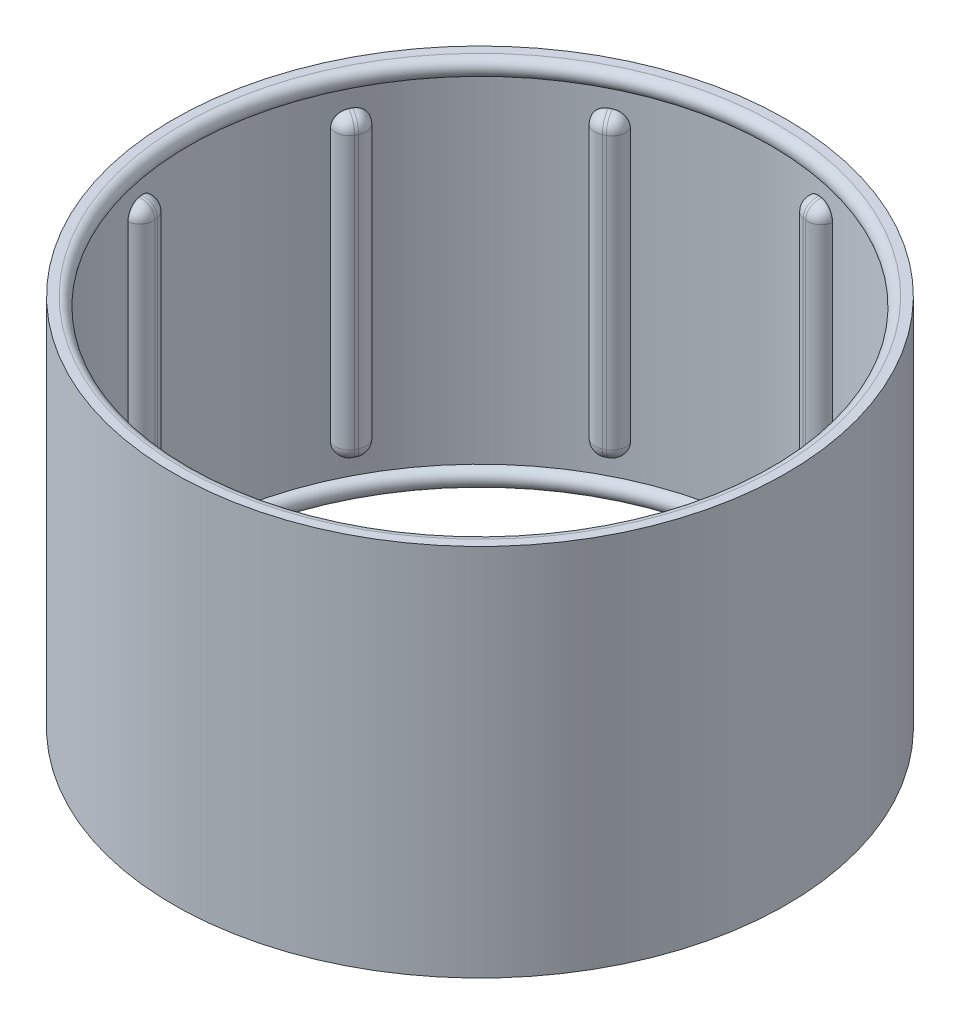
SolidWorks part; units mm, degrees
material "6061-T6 (SS)"
ref_plane "Front Plane" through (0, 0, 0) normal (0, 0, 1) x (1, 0, 0)
ref_plane "Top Plane" through (0, 0, 0) normal (0, 1, 0) x (1, 0, 0)
ref_plane "Right Plane" through (0, 0, 0) normal (1, 0, 0) x (0, 0, -1)
sketch "Sketch3" plane through (0, 0, 0) normal (0, 0, 1) x (1, 0, 0)
  line L0 (-52.07, 31.75) -> (-52.07, -31.75)
  line L1 (-50.546, 31.75) -> (-50.546, -31.75)
  line L2 (-50.546, -31.75) -> (-52.07, -31.75)
  line L3 (-52.07, 31.75) -> (-50.546, 31.75)
  line L4 (0, 0) -> (0, 24.1921) construction
  line L5 (-50.546, 31.75) -> (-50.546, 28.702)
  line L6 (-50.546, -28.702) -> (-50.546, -31.75)
  arc A0 (-50.546, 31.75) -> (-50.546, 28.702) centre (-50.546, 30.226) cw
  arc A1 (-50.546, -31.75) -> (-50.546, -28.702) centre (-50.546, -30.226) ccw
  point P6 (-50.546, 0)
  point P10 (-49.022, 30.226)
  dimension "D5" = 1.524
  dimension "D1" = 52.07
  dimension "D2" = 1.524
  dimension "D3" = 63.5
  dimension "D4" = 1.524
revolve "Revolve6" add sketch "Sketch3" angle 360 about L4
ref_plane "Plane2" through (0, 0, -152.4) normal (0, 0, 1) x (1, 0, 0)
ref_plane "Plane3" through (152.4, 0, 0) normal (1, 0, 0) x (0, 0, -1)
ref_plane "Plane7" through (152.4, 0, -152.4) normal (-0.7071, 0, 0.7071) x (0.7071, 0, 0.7071)
ref_plane "Plane8" through (35.8363, 0, -35.8363) normal (-0.7071, 0, 0.7071) x (0.7071, 0, 0.7071)
sketch "Sketch12" plane through (35.8363, 0, -35.8363) normal (-0.7071, 0, 0.7071) x (0.7071, 0, 0.7071)
  line L1 (-2.4676, 25.4) -> (2.6124, 25.4)
  line L7 (2.6124, 25.4) -> (2.6124, -25.4)
  line L11 (-2.4676, 25.4) -> (-2.4676, -25.4)
  line L12 (2.6124, -25.4) -> (-2.4676, -25.4)
  point P3 (-0.762, -25.4)
  dimension "D1" = 5.08
  dimension "D2" = 50.8
extrude "Boss-Extrude1" add sketch "Sketch12" along normal blind 2.54
fillet "Fillet1" radius 2.286 8 edges at (33.1246, 25.4, -36.6144) (34.0914, 25.4, -33.989) (36.7142, 25.4, -33.0197) (36.7142, -25.4, -33.0197) (33.1246, -25.4, -36.6144) (34.0914, -25.4, -33.989) (32.2954, 0, -35.7851) (35.8875, 0, -32.193)
pattern_circular "CirPattern1" count 10 over 360 about axis through (0, 0, 0) along (0, 1, 0) of "Fillet1", "Boss-Extrude1"
